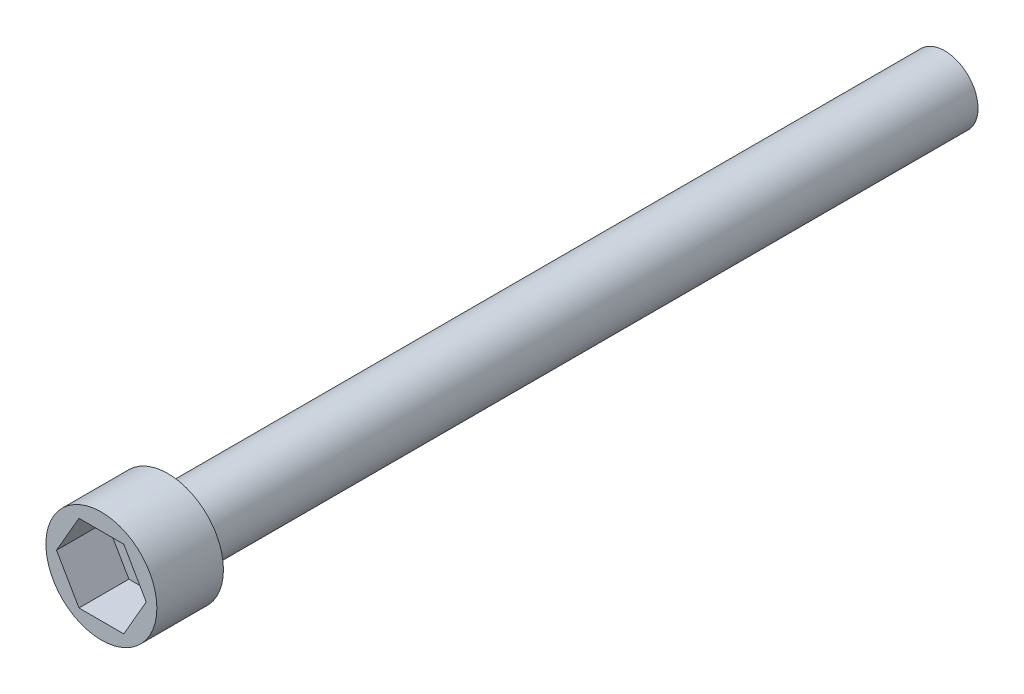
SolidWorks part; units mm, degrees
ref_plane "Plan de face" through (0, 0, 0) normal (0, 0, 1) x (1, 0, 0)
ref_plane "Plan de dessus" through (0, 0, 0) normal (0, 1, 0) x (1, 0, 0)
ref_plane "Plan de droite" through (0, 0, 0) normal (1, 0, 0) x (0, 0, -1)
sketch "Esquisse1" plane through (0, 0, 0) normal (0, 0, 1) x (1, 0, 0)
  circle A0 centre (0, 0) radius 3
  dimension "D1" = 6
extrude "Boss.-Extru.1" add sketch "Esquisse1" along normal blind 70
sketch "Esquisse2" plane through (0, 0, 70) normal (0, 0, 1) x (1, 0, 0)
  circle A0 centre (0, 0) radius 5
  dimension "D1" = 10
extrude "Boss.-Extru.2" add sketch "Esquisse2" along normal blind 6
sketch "Esquisse3" plane through (0, 0, 76) normal (0, 0, 1) x (1, 0, 0)
  line L1 (4.0415, 0) -> (2.0207, 3.5)
  line L2 (2.0207, 3.5) -> (-2.0207, 3.5)
  line L3 (-2.0207, 3.5) -> (-4.0415, 0)
  line L4 (-4.0415, 0) -> (-2.0207, -3.5)
  line L5 (-2.0207, -3.5) -> (2.0207, -3.5)
  line L6 (2.0207, -3.5) -> (4.0415, 0)
  circle A0 centre (0, 0) radius 3.5 construction
  dimension "D1" = 7
extrude "Enlèv. mat.-Extru.1" cut sketch "Esquisse3" against normal blind 4.5
